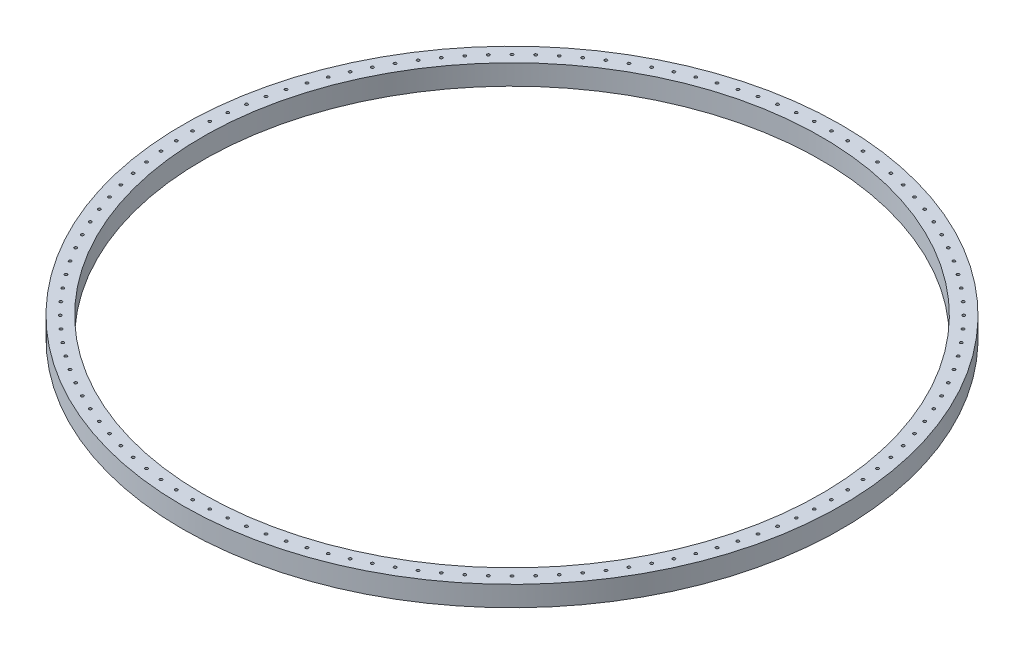
SolidWorks part; units mm, degrees
material "Ti-6Al-4VSolution treated and aged (SS)"
ref_plane "Front Plane" through (0, 0, 0) normal (0, 0, 1) x (1, 0, 0)
ref_plane "Top Plane" through (0, 0, 0) normal (0, 1, 0) x (1, 0, 0)
ref_plane "Right Plane" through (0, 0, 0) normal (1, 0, 0) x (0, 0, -1)
sketch "Sketch2" plane through (0, 0, 0) normal (0, 1, 0) x (1, 0, 0)
  circle A0 centre (0, 0) radius 787.527 construction
  circle A1 centre (0, 787.527) radius 3.4417
  circle A2 centre (41.216, 786.4477) radius 3.4417
  circle A3 centre (82.319, 783.2128) radius 3.4417
  circle A4 centre (123.1964, 777.8312) radius 3.4417
  circle A5 centre (163.7361, 770.3176) radius 3.4417
  circle A6 centre (203.827, 760.6927) radius 3.4417
  circle A7 centre (243.3592, 748.9827) radius 3.4417
  circle A8 centre (282.2244, 735.2198) radius 3.4417
  circle A9 centre (320.3161, 719.4417) radius 3.4417
  circle A10 centre (357.5298, 701.6917) radius 3.4417
  circle A11 centre (393.7635, 682.0184) radius 3.4417
  circle A12 centre (428.9179, 660.4757) radius 3.4417
  circle A13 centre (462.8968, 637.1227) radius 3.4417
  circle A14 centre (495.6068, 612.0234) radius 3.4417
  circle A15 centre (526.9584, 585.2466) radius 3.4417
  circle A16 centre (556.8657, 556.8657) radius 3.4417
  circle A17 centre (585.2466, 526.9584) radius 3.4417
  circle A18 centre (612.0234, 495.6068) radius 3.4417
  circle A19 centre (637.1227, 462.8968) radius 3.4417
  circle A20 centre (660.4757, 428.9179) radius 3.4417
  circle A21 centre (682.0184, 393.7635) radius 3.4417
  circle A22 centre (701.6917, 357.5298) radius 3.4417
  circle A23 centre (719.4417, 320.3161) radius 3.4417
  circle A24 centre (735.2198, 282.2244) radius 3.4417
  circle A25 centre (748.9827, 243.3592) radius 3.4417
  circle A26 centre (760.6927, 203.827) radius 3.4417
  circle A27 centre (770.3176, 163.7361) radius 3.4417
  circle A28 centre (777.8312, 123.1964) radius 3.4417
  circle A29 centre (783.2128, 82.319) radius 3.4417
  circle A30 centre (786.4477, 41.216) radius 3.4417
  circle A31 centre (787.527, 0) radius 3.4417
  circle A32 centre (786.4477, -41.216) radius 3.4417
  circle A33 centre (783.2128, -82.319) radius 3.4417
  circle A34 centre (777.8312, -123.1964) radius 3.4417
  circle A35 centre (770.3176, -163.7361) radius 3.4417
  circle A36 centre (760.6927, -203.827) radius 3.4417
  circle A37 centre (748.9827, -243.3592) radius 3.4417
  circle A38 centre (735.2198, -282.2244) radius 3.4417
  circle A39 centre (719.4417, -320.3161) radius 3.4417
  circle A40 centre (701.6917, -357.5298) radius 3.4417
  circle A41 centre (682.0184, -393.7635) radius 3.4417
  circle A42 centre (660.4757, -428.9179) radius 3.4417
  circle A43 centre (637.1227, -462.8968) radius 3.4417
  circle A44 centre (612.0234, -495.6068) radius 3.4417
  circle A45 centre (585.2466, -526.9584) radius 3.4417
  circle A46 centre (556.8657, -556.8657) radius 3.4417
  circle A47 centre (526.9584, -585.2466) radius 3.4417
  circle A48 centre (495.6068, -612.0234) radius 3.4417
  circle A49 centre (462.8968, -637.1227) radius 3.4417
  circle A50 centre (428.9179, -660.4757) radius 3.4417
  circle A51 centre (393.7635, -682.0184) radius 3.4417
  circle A52 centre (357.5298, -701.6917) radius 3.4417
  circle A53 centre (320.3161, -719.4417) radius 3.4417
  circle A54 centre (282.2244, -735.2198) radius 3.4417
  circle A55 centre (243.3592, -748.9827) radius 3.4417
  circle A56 centre (203.827, -760.6927) radius 3.4417
  circle A57 centre (163.7361, -770.3176) radius 3.4417
  circle A58 centre (123.1964, -777.8312) radius 3.4417
  circle A59 centre (82.319, -783.2128) radius 3.4417
  circle A60 centre (41.216, -786.4477) radius 3.4417
  circle A61 centre (0, -787.527) radius 3.4417
  circle A62 centre (-41.216, -786.4477) radius 3.4417
  circle A63 centre (-82.319, -783.2128) radius 3.4417
  circle A64 centre (-123.1964, -777.8312) radius 3.4417
  circle A65 centre (-163.7361, -770.3176) radius 3.4417
  circle A66 centre (-203.827, -760.6927) radius 3.4417
  circle A67 centre (-243.3592, -748.9827) radius 3.4417
  circle A68 centre (-282.2244, -735.2198) radius 3.4417
  circle A69 centre (-320.3161, -719.4417) radius 3.4417
  circle A70 centre (-357.5298, -701.6917) radius 3.4417
  circle A71 centre (-393.7635, -682.0184) radius 3.4417
  circle A72 centre (-428.9179, -660.4757) radius 3.4417
  circle A73 centre (-462.8968, -637.1227) radius 3.4417
  circle A74 centre (-495.6068, -612.0234) radius 3.4417
  circle A75 centre (-526.9584, -585.2466) radius 3.4417
  circle A76 centre (-556.8657, -556.8657) radius 3.4417
  circle A77 centre (-585.2466, -526.9584) radius 3.4417
  circle A78 centre (-612.0234, -495.6068) radius 3.4417
  circle A79 centre (-637.1227, -462.8968) radius 3.4417
  circle A80 centre (-660.4757, -428.9179) radius 3.4417
  circle A81 centre (-682.0184, -393.7635) radius 3.4417
  circle A82 centre (-701.6917, -357.5298) radius 3.4417
  circle A83 centre (-719.4417, -320.3161) radius 3.4417
  circle A84 centre (-735.2198, -282.2244) radius 3.4417
  circle A85 centre (-748.9827, -243.3592) radius 3.4417
  circle A86 centre (-760.6927, -203.827) radius 3.4417
  circle A87 centre (-770.3176, -163.7361) radius 3.4417
  circle A88 centre (-777.8312, -123.1964) radius 3.4417
  circle A89 centre (-783.2128, -82.319) radius 3.4417
  circle A90 centre (-786.4477, -41.216) radius 3.4417
  circle A91 centre (-787.527, 0) radius 3.4417
  circle A92 centre (-786.4477, 41.216) radius 3.4417
  circle A93 centre (-783.2128, 82.319) radius 3.4417
  circle A94 centre (-777.8312, 123.1964) radius 3.4417
  circle A95 centre (-770.3176, 163.7361) radius 3.4417
  circle A96 centre (-760.6927, 203.827) radius 3.4417
  circle A97 centre (-748.9827, 243.3592) radius 3.4417
  circle A98 centre (-735.2198, 282.2244) radius 3.4417
  circle A99 centre (-719.4417, 320.3161) radius 3.4417
  circle A100 centre (-701.6917, 357.5298) radius 3.4417
  circle A101 centre (-682.0184, 393.7635) radius 3.4417
  circle A102 centre (-660.4757, 428.9179) radius 3.4417
  circle A103 centre (-637.1227, 462.8968) radius 3.4417
  circle A104 centre (-612.0234, 495.6068) radius 3.4417
  circle A105 centre (-585.2466, 526.9584) radius 3.4417
  circle A106 centre (-556.8657, 556.8657) radius 3.4417
  circle A107 centre (-526.9584, 585.2466) radius 3.4417
  circle A108 centre (-495.6068, 612.0234) radius 3.4417
  circle A109 centre (-462.8968, 637.1227) radius 3.4417
  circle A110 centre (-428.9179, 660.4757) radius 3.4417
  circle A111 centre (-393.7635, 682.0184) radius 3.4417
  circle A112 centre (-357.5298, 701.6917) radius 3.4417
  circle A113 centre (-320.3161, 719.4417) radius 3.4417
  circle A114 centre (-282.2244, 735.2198) radius 3.4417
  circle A115 centre (-243.3592, 748.9827) radius 3.4417
  circle A116 centre (-203.827, 760.6927) radius 3.4417
  circle A117 centre (-163.7361, 770.3176) radius 3.4417
  circle A118 centre (-123.1964, 777.8312) radius 3.4417
  circle A119 centre (-82.319, 783.2128) radius 3.4417
  circle A120 centre (-41.216, 786.4477) radius 3.4417
  circle A121 centre (0, 0) radius 812.527
  circle A122 centre (0, 0) radius 762.527
  point P246 (0, 0)
  dimension "D1" = 1575.054
  dimension "D3" = 6.8834
  dimension "D4" = 25
  dimension "D5" = 25
  dimension "D2" = 120
extrude "Boss-Extrude1" add sketch "Sketch2" along normal blind 50 contours A121 A122 A1 A2 A3 A4 A5 A6 A7 A8 A9 A10 A11 A12 A13 A14 A15 A16 A17 A18 A19 A20 A21 A22 A23 A24
